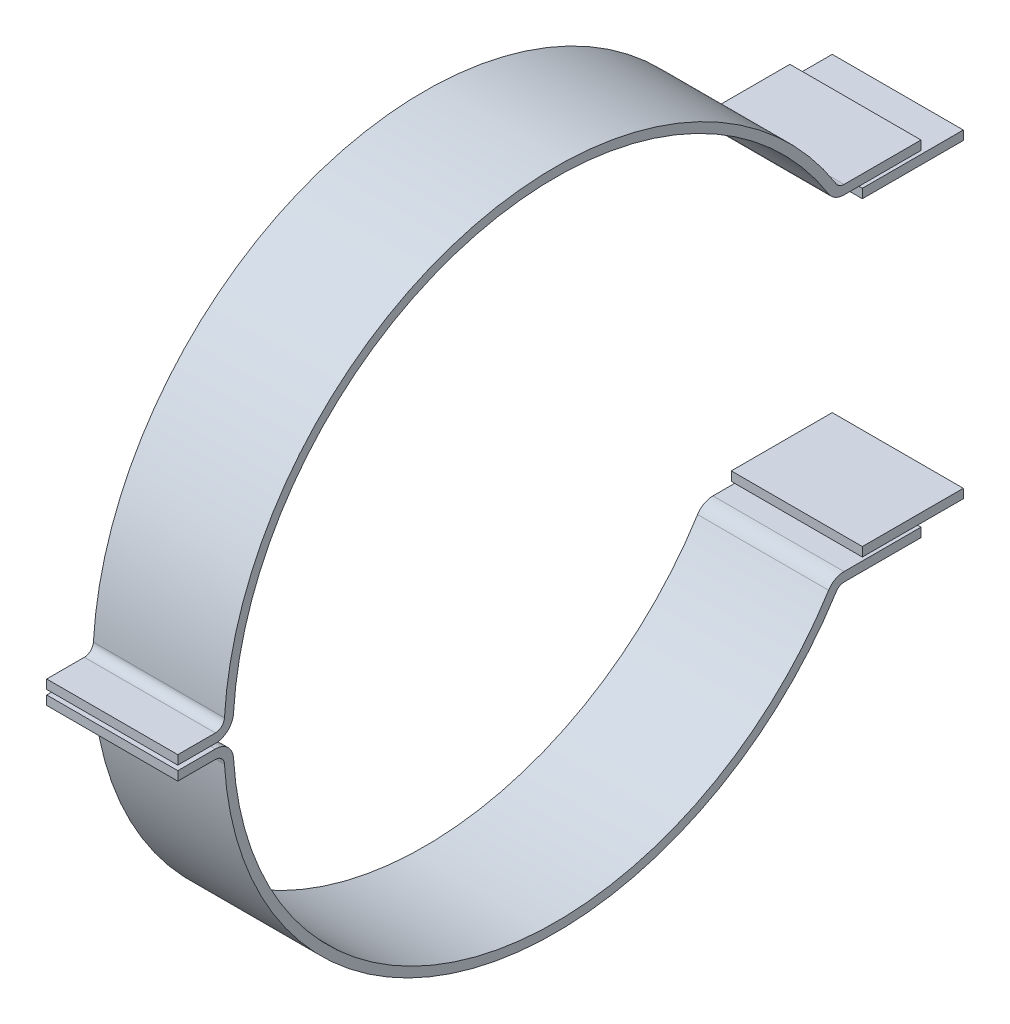
SolidWorks part; units mm, degrees
ref_plane "Front Plane" through (0, 0, 0) normal (0, 0, 1) x (1, 0, 0)
ref_plane "Top Plane" through (0, 0, 0) normal (0, 1, 0) x (1, 0, 0)
ref_plane "Right Plane" through (0, 0, 0) normal (1, 0, 0) x (0, 0, -1)
sketch "Sketch1" plane through (0, 0, 0) normal (1, 0, 0) x (0, 0, -1)
  line L0 (122.3991, -74.9807) -> (122.3991, -64.9807)
  line L1 (-652.7764, 116.7958) -> (-694.0578, 116.7958)
  line L2 (37.8869, -64.9807) -> (122.3991, -64.9807)
  line L3 (-652.7764, 126.7958) -> (-694.0578, 126.7958)
  line L4 (-694.0578, 116.7958) -> (-694.0578, 126.7958)
  line L5 (37.8869, -74.9807) -> (122.3991, -74.9807)
  line L6 (168.8776, -61.2452) -> (168.8776, -51.2452)
  line L7 (57.996, -61.2452) -> (57.996, -51.2452)
  line L8 (57.996, -61.2452) -> (168.8776, -61.2452)
  line L9 (57.996, -51.2452) -> (168.8776, -51.2452)
  line L10 (-694.0578, 111.5878) -> (-694.0578, 101.5878)
  line L11 (-652.7764, 101.5878) -> (-694.0578, 101.5878)
  line L12 (-652.7764, 111.5878) -> (-694.0578, 111.5878)
  line L23 (57.996, 279.6287) -> (168.8776, 279.6287)
  line L24 (57.996, 289.6287) -> (168.8776, 289.6287)
  line L26 (57.996, 289.6287) -> (57.996, 279.6287)
  line L28 (168.8776, 289.6287) -> (168.8776, 279.6287)
  line L32 (37.8869, 303.3643) -> (122.3991, 303.3643)
  line L33 (37.8869, 293.3643) -> (122.3991, 293.3643)
  line L34 (122.3991, 303.3643) -> (122.3991, 293.3643)
  arc A0 (-632.8129, 135.5882) -> (-652.7764, 116.7958) centre (-652.7764, 136.7958) cw
  arc A1 (-652.7764, 126.7958) -> (-642.7946, 136.192) centre (-652.7764, 136.7958) ccw
  arc A2 (20.9524, -74.3401) -> (37.8869, -64.9807) centre (37.8869, -84.9807) cw
  arc A3 (29.4196, -79.6604) -> (37.8869, -74.9807) centre (37.8869, -84.9807) cw
  arc A4 (29.4196, -79.6604) -> (-642.7946, 92.1916) centre (-279.0961, 114.1918) cw
  arc A5 (20.9524, -74.3401) -> (-632.8129, 92.7954) centre (-279.0961, 114.1918) cw
  arc A6 (-652.7764, 101.5878) -> (-642.7946, 92.1916) centre (-652.7764, 91.5878) cw
  arc A7 (-632.8129, 92.7954) -> (-652.7764, 111.5878) centre (-652.7764, 91.5878) ccw
  arc A10 (20.9524, 302.7237) -> (-632.8129, 135.5882) centre (-279.0961, 114.1918) ccw
  arc A11 (29.4196, 308.044) -> (-642.7946, 136.192) centre (-279.0961, 114.1918) ccw
  arc A12 (29.4196, 308.044) -> (37.8869, 303.3643) centre (37.8869, 313.3643) ccw
  arc A13 (20.9524, 302.7237) -> (37.8869, 293.3643) centre (37.8869, 313.3643) ccw
  dimension "D2" = 20
  dimension "D3" = 10
  dimension "D5" = 10
  dimension "D6" = 20
  dimension "D1" = 10
extrude "Boss-Extrude1" add sketch "Sketch1" along normal blind 144
